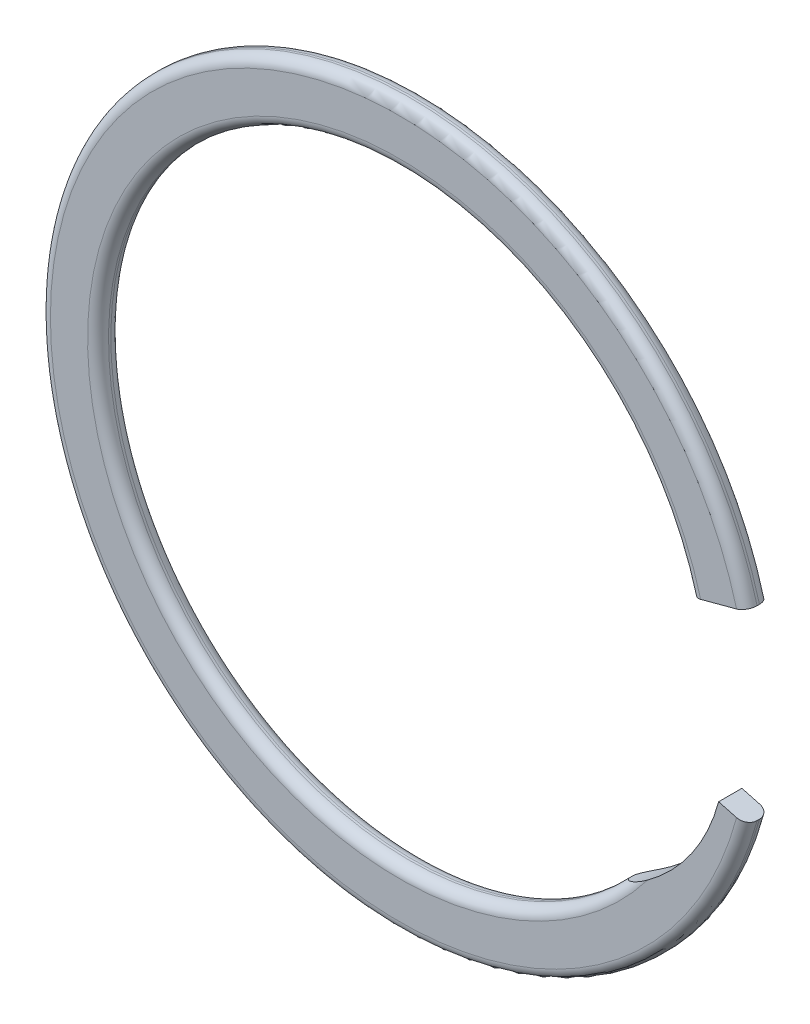
SolidWorks part; units mm, degrees
ref_plane "Front Plane" through (0, 0, 0) normal (0, 0, 1) x (1, 0, 0)
ref_plane "Top Plane" through (0, 0, 0) normal (0, 1, 0) x (1, 0, 0)
ref_plane "Right Plane" through (0, 0, 0) normal (1, 0, 0) x (0, 0, -1)
sketch "Sketch1" plane through (0, 0, 0) normal (0, 0, 1) x (1, 0, 0)
  line L0 (5.9309, 0) -> (7.0739, 0) construction
  line L1 (-5.9309, 0) -> (-7.0739, 0) construction
  line L2 (5.7288, 1.535) -> (6.8329, 1.8309)
  line L3 (5.7288, -1.535) -> (6.8329, -1.8309)
  line L4 (6.2808, -1.6829) -> (5.5599, -4.3735) construction
  line L5 (5.5599, -4.3735) -> (4.3367, -4.0458) construction
  circle A0 centre (0, 0) radius 5.9309
  circle A1 centre (0, 0) radius 7.0739
  arc A2 (6.2808, -1.6829) -> (4.3367, -4.0458) centre (2.7101, -0.7262) cw
  dimension "Free Diameter" = 11.8618
  dimension "Radial Wall" = 1.143
  dimension "D3" = 30
sketch "Sketch2" plane through (0, 0, 0) normal (0, 0, 1) x (1, 0, 0)
  line L0 (5.7288, -1.535) -> (6.8329, -1.8309) construction
  line L1 (5.7288, 1.535) -> (6.8329, 1.8309) construction
  line L2 (6.2808, -1.6829) -> (6.8329, -1.8309)
  line L3 (5.7288, 1.535) -> (6.8329, 1.8309)
  circle A0 centre (0, 0) radius 7.0739 construction
  arc A1 (4.3367, -4.0458) -> (6.2808, -1.6829) centre (2.7101, -0.7262) ccw construction
  circle A2 centre (0, 0) radius 5.9309 construction
  arc A3 (6.8329, 1.8309) -> (6.8329, -1.8309) centre (0, 0) ccw
  arc A4 (4.3367, -4.0458) -> (6.2808, -1.6829) centre (2.7101, -0.7262) ccw
  arc A5 (5.7288, 1.535) -> (4.3367, -4.0458) centre (0, 0) ccw
  arc A6 (5.7288, 1.535) -> (4.3367, -4.0458) centre (0, 0) cw construction
  arc A7 (6.8329, 1.8309) -> (6.8329, -1.8309) centre (0, 0) cw construction
extrude "Extrude1" add sketch "Sketch2" along normal mid plane 0.4572
fillet "Fillet1" radius 0.2057 4 edges at (-7.0739, 0, -0.2286) (-7.0739, 0, 0.2286) (-5.7546, 1.4354, -0.2286) (-5.7546, 1.4354, 0.2286)
sketch "Sketch3" plane through (0, 0, 0) normal (1, 0, 0) x (0, 0, -1)
  line L0 (-0.2794, 6.35) -> (-0.2794, 5.9944)
  line L1 (-0.2794, 5.9944) -> (0.2794, 5.9944)
  line L2 (0.2794, 5.9944) -> (0.2794, 6.35)
  line L3 (0.2794, 6.35) -> (16.6687, 6.35)
  line L4 (16.6687, 6.35) -> (16.6687, 0)
  line L5 (-0.2794, 6.35) -> (-1.4287, 6.35)
  line L6 (-1.4287, 6.35) -> (-2.3813, 5.3975)
  line L7 (-2.3813, 5.3975) -> (-2.3812, 0)
  line L8 (-2.3812, 0) -> (16.6687, 0)
  line L9 (-2.3812, 0) -> (16.6687, 0) construction
  line L10 (0, 0) -> (0, 5.9944) construction
  dimension "Groove width" = 0.5588
  dimension "groove dia" = 11.9888
  dimension "shaft dia" = 12.7
  dimension "D1" = 45
  dimension "D2" = 10.795
  dimension "D3" = 19.05
  dimension "D4" = 2.3813
revolve "Revolve1" [suppressed] add sketch "Sketch3" angle 360 about L8
equation "\"D1@Fillet1\" = (\"Ring Thickness@Extrude1\"*.9)/2"
equation "\"D2@Sketch3\" = \"shaft dia@Sketch3\"*.85"
equation "\"D4@Sketch3\"= \"D3@Sketch3\" / 8"
